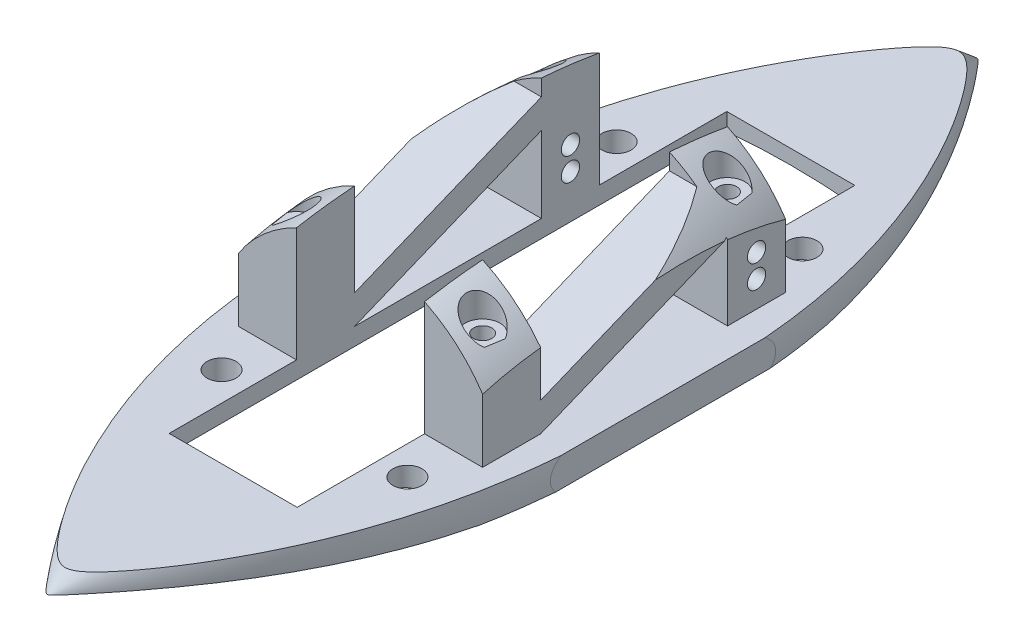
SolidWorks part; units mm, degrees
material "Custom Plastic"
ref_plane "Front Plane" through (0, 0, 0) normal (0, 0, 1) x (1, 0, 0)
ref_plane "Top Plane" through (0, 0, 0) normal (0, 1, 0) x (1, 0, 0)
ref_plane "Right Plane" through (0, 0, 0) normal (1, 0, 0) x (0, 0, -1)
sketch "Sketch2" plane through (0, 0, 0) normal (0, 0, 1) x (1, 0, 0)
  line L1 (-16.51, 1.5875) -> (16.51, 1.5875)
  line L2 (-16.51, 1.5875) -> (-16.51, -1.5875)
  line L3 (-16.51, -1.5875) -> (16.51, -1.5875)
  line L4 (16.51, 1.5875) -> (16.51, -1.5875)
  line L5 (-16.51, 1.5875) -> (16.51, -1.5875) construction
  line L6 (-16.51, -1.5875) -> (16.51, 1.5875) construction
  point P0 (0, 0)
  dimension "D1" = 3.175
  dimension "D2" = 33.02
extrude "Boss-Extrude1" add sketch "Sketch2" along normal blind 101.6
sketch "Sketch3" plane through (0, 0, 101.6) normal (0, 0, 1) x (1, 0, 0)
  line L0 (0, 0) -> (0, -76.2) construction
  circle A0 centre (0, -76.2) radius 76.2
  dimension "D1" = 76.2
extrude "Cut-Extrude1" cut sketch "Sketch3" against normal through all
sketch "Sketch5" plane through (0, 1.5875, 0) normal (0, 1, 0) x (1, 0, 0)
  line L0 (0, 0) -> (0, -34.925) construction
  line L1 (6.9977, -44.4246) -> (10.1727, -44.4246) construction
  line L2 (-6.9977, -25.4254) -> (6.9977, -25.4254) construction
  line L3 (-6.9977, -25.4254) -> (-6.9977, -44.4246) construction
  line L4 (-6.9977, -44.4246) -> (6.9977, -44.4246) construction
  line L5 (6.9977, -25.4254) -> (6.9977, -44.4246) construction
  line L6 (-6.9977, -25.4254) -> (6.9977, -44.4246) construction
  line L7 (-6.9977, -44.4246) -> (6.9977, -25.4254) construction
  line L8 (10.1727, -44.4246) -> (10.1727, -37.4142) construction
  line L9 (-13.3477, -40.5892) -> (-6.9977, -40.5892)
  line L10 (13.3477, -40.5892) -> (6.9977, -40.5892)
  line L11 (13.3477, -40.5892) -> (13.3477, -34.2392)
  line L12 (13.3477, -34.2392) -> (6.9977, -34.2392)
  line L13 (6.9977, -40.5892) -> (6.9977, -34.2392)
  line L14 (13.3477, -40.5892) -> (6.9977, -34.2392) construction
  line L15 (13.3477, -34.2392) -> (6.9977, -40.5892) construction
  line L16 (-6.9977, -40.5892) -> (-6.9977, -34.2392)
  line L17 (-13.3477, -40.5892) -> (-6.9977, -34.2392) construction
  line L18 (-13.3477, -34.2392) -> (-6.9977, -40.5892) construction
  line L19 (-13.3477, -34.2392) -> (-6.9977, -34.2392)
  line L20 (-13.3477, -40.5892) -> (-13.3477, -34.2392)
  line L21 (-10.1727, -44.4246) -> (-10.1727, -37.4142) construction
  line L22 (-6.9977, -44.4246) -> (-10.1727, -44.4246) construction
  line L23 (-16.51, -50.8) -> (16.51, -50.8) construction
  line L24 (-16.51, -101.6) -> (-16.51, 0) construction
  line L25 (16.51, -101.6) -> (16.51, 0) construction
  line L26 (-13.3477, -61.0108) -> (-6.9977, -61.0108)
  line L27 (-13.3477, -67.3608) -> (-6.9977, -61.0108) construction
  line L28 (-13.3477, -61.0108) -> (-6.9977, -67.3608) construction
  line L29 (-6.9977, -61.0108) -> (-6.9977, -67.3608)
  line L30 (-13.3477, -67.3608) -> (-6.9977, -67.3608)
  line L31 (-13.3477, -61.0108) -> (-13.3477, -67.3608)
  line L32 (13.3477, -67.3608) -> (6.9977, -61.0108) construction
  line L33 (13.3477, -61.0108) -> (6.9977, -67.3608) construction
  line L34 (6.9977, -61.0108) -> (6.9977, -67.3608)
  line L35 (13.3477, -67.3608) -> (6.9977, -67.3608)
  line L36 (13.3477, -61.0108) -> (13.3477, -67.3608)
  line L37 (13.3477, -61.0108) -> (6.9977, -61.0108)
  dimension "D1" = 13.9954
  dimension "D2" = 18.9992
  dimension "D3" = 34.925
  dimension "D4" = 3.175
  dimension "D5" = 7.0104
  dimension "D6" = 6.35
extrude "Boss-Extrude2" add sketch "Sketch5" along normal blind 15.24
sketch "Sketch6" plane through (13.3477, 0, 0) normal (1, 0, 0) x (0, 0, -1)
  line L0 (-61.0108, 1.5875) -> (-40.5892, 1.5875) construction
  line L1 (-40.5892, 1.5875) -> (-40.5892, 9.923) construction
  line L2 (-40.5892, 16.8275) -> (-40.5892, 1.5875) construction
  line L3 (-40.5892, 9.923) -> (-40.5892, 13.098) construction
  line L4 (-61.0108, 1.5875) -> (-61.0108, 4.7625) construction
  line L5 (-61.0108, 16.8275) -> (-61.0108, 1.5875) construction
  line L10 (-61.0108, 1.5875) -> (-61.0108, 4.7625)
  line L11 (-61.0108, 1.5875) -> (-40.5892, 9.923)
  line L12 (-61.0108, 4.7625) -> (-40.5892, 13.098)
  line L13 (-40.5892, 9.923) -> (-40.5892, 13.098)
  dimension "D1" = 8.3355
  dimension "D2" = 3.175
extrude "Boss-Extrude3" add sketch "Sketch6" against normal blind 6.35
sketch "Sketch4" plane through (0, 0, 0) normal (1, 0, 0) x (0, 0, -1)
  line L0 (0, 0) -> (-48.26, 0) construction
  line L1 (-48.26, 0) -> (-48.26, 16.51) construction
  line L2 (-48.26, 16.51) -> (-53.34, 16.51)
  line L3 (-50.8, 16.51) -> (-50.8, 0) construction
  line L4 (-48.26, 0) -> (-53.34, 0) construction
  line L5 (-101.6, 0) -> (-53.34, 0) construction
  line L6 (0, 0) -> (-101.6, 0) construction
  line L7 (0, 0) -> (0, -0.254) construction
  line L8 (0, -1.5875) -> (0, 1.5875) construction
  line L9 (0, -0.254) -> (-101.6, -0.254) construction
  line L10 (0, 0) -> (0, 25.4)
  line L11 (0, 25.4) -> (-101.6, 25.4)
  line L12 (-101.6, 25.4) -> (-101.6, 0)
  arc A0 (-48.26, 16.51) -> (0, 0) centre (-45.1787, -53.272) cw
  arc A1 (-53.34, 16.51) -> (-101.6, 0) centre (-56.4213, -53.272) ccw
  dimension "D3" = 69.85
  dimension "D5" = 0.254
  dimension "D1" = 48.26
  dimension "D2" = 16.51
  dimension "D4" = 2.54
  dimension "D6" = 101.6
  dimension "D7" = 25.4
mirror "Mirror4" about plane through (0, 0, 0) normal (1, 0, 0) of "Boss-Extrude3"
revolve "Cut-Revolve1" cut sketch "Sketch4" angle 100 about L9 other way angle 100
sketch "Sketch7" plane through (0, 1.5875, 0) normal (0, 1, 0) x (1, 0, 0)
  line L0 (0, 0) -> (0, -50.8) construction
  line L2 (-6.9977, -81.28) -> (6.9977, -81.28)
  line L3 (-6.9977, -81.28) -> (-6.9977, -20.32)
  line L4 (-6.9977, -20.32) -> (6.9977, -20.32)
  line L5 (6.9977, -81.28) -> (6.9977, -20.32)
  line L6 (-6.9977, -81.28) -> (6.9977, -20.32) construction
  line L7 (-6.9977, -20.32) -> (6.9977, -81.28) construction
  dimension "D1" = 50.8
  dimension "D2" = 13.9954
  dimension "D3" = 60.96
extrude "Cut-Extrude2" cut sketch "Sketch7" against normal up to next
sketch "Sketch8" plane through (13.3477, 0, 0) normal (1, 0, 0) x (0, 0, -1)
  line L0 (0, 0) -> (-34.2392, 0) construction
  line L1 (-37.4142, 0) -> (-37.4142, 6.985) construction
  line L2 (-34.2392, 0) -> (-40.5892, 0) construction
  line L3 (-40.5892, 0) -> (-40.5892, 1.5875) construction
  line L4 (-34.2392, 0) -> (-34.2392, 1.5875) construction
  line L5 (-34.2392, 8.5142) -> (-34.2392, 1.5875) construction
  line L6 (-37.4142, 0) -> (-37.4142, 4.445) construction
  line L7 (-40.5892, 9.7508) -> (-40.5892, 1.5875) construction
  circle A0 centre (-37.4142, 6.985) radius 1
  circle A1 centre (-37.4142, 4.445) radius 1
  dimension "D3" = 2
  dimension "D4" = 2
  dimension "D1" = 6.985
  dimension "D2" = 4.445
extrude "Cut-Extrude3" cut sketch "Sketch8" against normal up to surface and the other way through all up to face at (-13.3477, 5.5146, 38.208)
sketch "Sketch9" plane through (0, 1.5875, 0) normal (0, 1, 0) x (1, 0, 0)
  line L0 (-16.51, -50.8) -> (-10.16, -50.8) construction
  line L1 (-16.51, -61.9559) -> (-16.51, -39.6441) construction
  line L2 (-10.16, -50.8) -> (16.51, -50.8) construction
  line L3 (-10.16, -29.21) -> (-10.16, -72.39) construction
  line L5 (16.51, -61.9559) -> (16.51, -39.6441) construction
  line L6 (0, -20.32) -> (0, -81.28) construction
  line L7 (6.9977, -20.32) -> (-6.9977, -20.32) construction
  line L8 (-6.9977, -81.28) -> (6.9977, -81.28) construction
  line L9 (16.51, -50.8) -> (10.16, -50.8) construction
  line L10 (10.16, -29.21) -> (10.16, -72.39) construction
  circle A1 centre (-10.16, -72.39) radius 1.5875
  circle A2 centre (-10.16, -29.21) radius 1.5875
  circle A3 centre (10.16, -72.39) radius 1.5875
  circle A4 centre (10.16, -29.21) radius 1.5875
  dimension "D4" = 3.175
  dimension "D1" = 6.35
  dimension "D2" = 21.59
extrude "Cut-Extrude4" cut sketch "Sketch9" against normal up to next
sketch "Sketch11" plane through (0, 1.5875, 0) normal (0, 1, 0) x (1, 0, 0)
  line L0 (-6.9977, -37.4142) -> (-13.3477, -37.4142) construction
  line L1 (-6.9977, -40.5892) -> (-6.9977, -34.2392) construction
  line L2 (-13.3477, -34.2392) -> (-13.3477, -40.5892) construction
  line L3 (6.9977, -37.4142) -> (13.3477, -37.4142) construction
  line L4 (6.9977, -34.2392) -> (6.9977, -40.5892) construction
  line L5 (13.3477, -40.5892) -> (13.3477, -34.2392) construction
  line L6 (-16.51, -50.8) -> (16.51, -50.8) construction
  line L7 (-16.51, -61.9559) -> (-16.51, -39.6441) construction
  line L8 (16.51, -61.9559) -> (16.51, -39.6441) construction
  line L9 (-10.1727, -37.4142) -> (-10.1727, -50.8) construction
  line L10 (-10.1727, -50.8) -> (0, -50.8) construction
  circle A0 centre (-10.1727, -37.4142) radius 1.905
  circle A1 centre (10.1727, -37.4142) radius 1.905
  circle A2 centre (10.1727, -64.1858) radius 1.905
  circle A3 centre (-10.1727, -64.1858) radius 1.905
  dimension "D1" = 3.81
  dimension "D2" = 3.81
extrude "Cut-Extrude5" cut sketch "Sketch11" along normal up to next from offset 9.525
sketch "Sketch12" plane through (0, 11.1125, 0) normal (0, 1, 0) x (1, 0, 0)
  line L0 (16.51, -50.8) -> (-16.51, -50.8) construction
  line L1 (16.51, -61.9559) -> (16.51, -39.6441) construction
  line L4 (-16.51, -61.9559) -> (-16.51, -39.6441) construction
  line L5 (0, 0) -> (0, -101.6) construction
  circle A0 centre (10.1727, -64.1858) radius 1
  circle A2 centre (-10.1727, -64.1858) radius 1
  circle A3 centre (-10.1727, -37.4142) radius 1
  circle A4 centre (10.1727, -37.4142) radius 1
  spline S0 degree 3 poles (15.473, -69.8429) (14.9036, -72.7924) (14.1525, -75.672) (12.2977, -81.2973) (11.1939, -84.043) (9.268, -88.0609) (8.5809, -89.3834) (7.4805, -91.3415) (7.1017, -91.9905) (6.3239, -93.2741) (5.9247, -93.9093) (4.6957, -95.7951) (3.8343, -97.027) (2.4811, -98.8295) (2.02, -99.4231) (1.3102, -100.2989) (1.0709, -100.5889) (0.7022, -101.0153) (0.5781, -101.1565) (0.3822, -101.3593) (0.3158, -101.4256) (0.2066, -101.5148) (0.1682, -101.5431) (0.0852, -101.5867) (0.0388, -101.6018) (-0.0566, -101.5979) (-0.1017, -101.5797) (-0.1833, -101.5327) (-0.2211, -101.5037) (-0.3291, -101.4129) (-0.3952, -101.3464) (-0.5898, -101.1434) (-0.7137, -101.0021) (-1.0817, -100.576) (-1.3204, -100.2865) (-2.0288, -99.4119) (-2.4893, -98.8188) (-3.8392, -97.0201) (-4.6965, -95.7937) (-6.3292, -93.2887) (-7.1044, -92.0098) (-8.2055, -90.0517) (-8.5624, -89.392) (-9.252, -88.0661) (-9.5852, -87.399) (-11.1941, -84.0432) (-12.2991, -81.2938) (-14.1542, -75.6662) (-14.9044, -72.788) (-15.473, -69.8429) knots 0 0 0 0 0.125 0.125 0.25 0.25 0.3125 0.3125 0.34375 0.34375 0.375 0.375 0.4375 0.4375 0.46875 0.46875 0.484375 0.484375 0.492187 0.492187 0.496094 0.496094 0.498047 0.498047 0.5 0.5 0.501953 0.501953 0.503906 0.503906 0.507812 0.507812 0.515625 0.515625 0.53125 0.53125 0.5625 0.5625 0.625 0.625 0.6875 0.6875 0.71875 0.71875 0.75 0.75 0.875 0.875 1 1 1 1 construction
  dimension "D1" = 2
extrude "Cut-Extrude6" cut sketch "Sketch12" against normal blind 4.445
